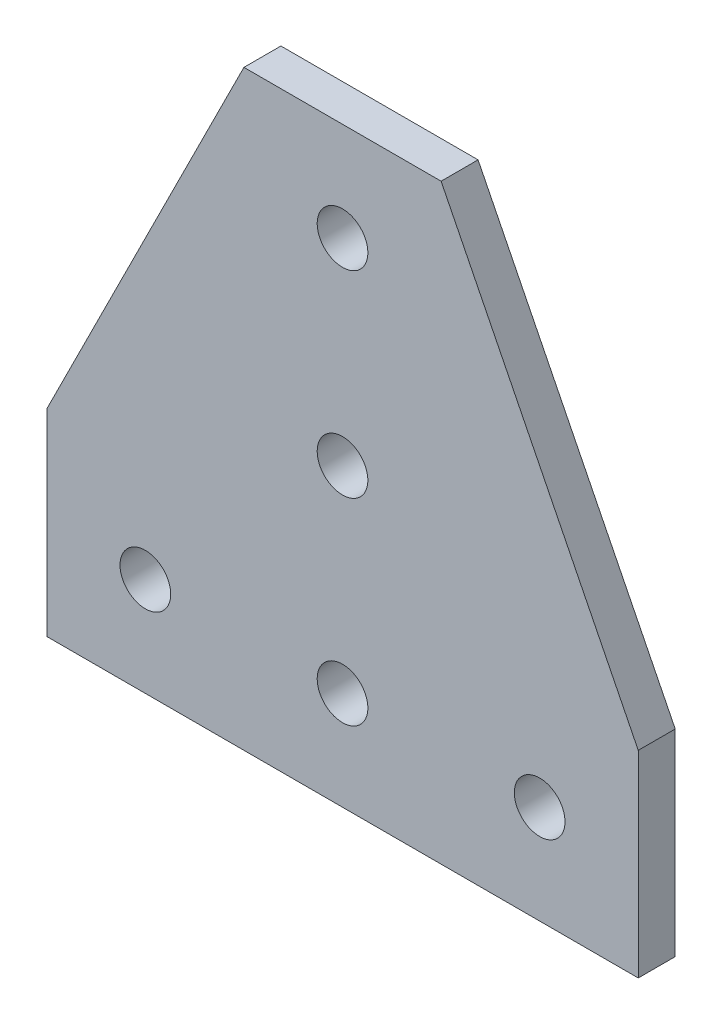
SolidWorks part; units mm, degrees
ref_plane "Front Plane" through (0, 0, 0) normal (0, 0, 1) x (1, 0, 0)
ref_plane "Top Plane" through (0, 0, 0) normal (0, 1, 0) x (1, 0, 0)
ref_plane "Right Plane" through (0, 0, 0) normal (1, 0, 0) x (0, 0, -1)
sketch "Sketch1" plane through (0, 0, 0) normal (0, 0, 1) x (1, 0, 0)
  line L0 (12.7, 25.4) -> (25.4, 25.4)
  line L1 (25.4, 25.4) -> (25.4, -50.8)
  line L2 (25.4, -50.8) -> (-12.7, -50.8)
  line L3 (-12.7, -50.8) -> (-12.7, -25.4)
  line L4 (-12.7, -25.4) -> (12.7, 25.4)
  dimension "D1" = 12.7
  dimension "height" = 76.2
  dimension "width" = 38.1
  dimension "flat" = 25.4
extrude "Extrude1" add sketch "Sketch1" against normal blind 4.7625
mirror "Mirror1" about plane through (25.4, 25.4, -4.7625) normal (1, 0, 0) of bodies 101
sketch "Sketch2" plane through (0, 0, -4.7625) normal (0, 0, -1) x (-1, 0, 0)
  line L0 (-25.4, 25.4) -> (-25.4, -38.1) construction
  line L1 (-38.1, 25.4) -> (-12.7, 25.4) construction
  line L2 (12.7, -38.1) -> (-25.4, -38.1) construction
  line L3 (12.7, -25.4) -> (12.7, -50.8) construction
  circle A0 centre (-25.4, -38.1) radius 3.2639
  circle A1 centre (0, -38.1) radius 3.2639
  circle A2 centre (25.4, -38.1) radius 3.2639
  circle A3 centre (-25.4, -12.7) radius 3.2639
  circle A4 centre (-25.4, 12.7) radius 3.2639
  dimension "hole" = 6.5278
  dimension "D2" = 25.4
  dimension "D3" = 25.4
  dimension "D4" = 25.4
  dimension "center to center" = 25.4
extrude "single 90" [suppressed] cut sketch "Sketch2" against normal through all
sketch "Sketch3" plane through (0, 0, -4.7625) normal (0, 0, -1) x (-1, 0, 0)
  line L0 (-63.5, -38.1) -> (12.7, -38.1) construction
  line L1 (-63.5, -25.4) -> (-63.5, -50.8) construction
  line L2 (12.7, -25.4) -> (12.7, -50.8) construction
  line L3 (-25.4, 25.4) -> (-25.4, -38.1) construction
  line L4 (-38.1, 25.4) -> (-12.7, 25.4) construction
  circle A0 centre (-25.4, -38.1) radius 3.2639
  circle A1 centre (-25.4, -12.7) radius 3.2639
  circle A2 centre (-25.4, 12.7) radius 3.2639
  circle A3 centre (-50.8, -38.1) radius 3.2639
  circle A4 centre (0, -38.1) radius 3.2639
  dimension "D1" = 6.5278
  dimension "D3" = 25.4
  dimension "D4" = 25.4
  dimension "D5" = 25.4
  dimension "center to center" = 25.4
extrude "single tee" cut sketch "Sketch3" against normal through all
sketch "Sketch4" [suppressed] plane through (0, 0, -6.35) normal (0, 0, -1) x (-1, 0, 0)
  line L0 (19.05, -76.2) -> (19.05, -57.15) construction
  line L1 (12.7, -25.4) -> (12.7, -50.8) construction
  line L2 (19.05, -57.15) -> (19.05, -38.1) construction
  line L3 (-114.3, 38.1) -> (-38.1, 38.1) construction
  line L4 (-38.1, 25.4) -> (-12.7, 25.4) construction
  line L5 (-38.1, 38.1) -> (-19.05, 38.1) construction
  line L6 (-76.2, 38.1) -> (-76.2, -66.675) construction
  line L7 (19.05, -66.675) -> (-76.2, -66.675) construction
  line L8 (19.05, -47.625) -> (-28.575, -47.625) construction
  line L9 (-28.575, 38.1) -> (-28.575, -47.625) construction
  circle A0 centre (-76.2, -66.675) radius 4.1656
  circle A1 centre (-28.575, -47.625) radius 4.1656
  circle A2 centre (-28.575, -66.675) radius 4.1656
  circle A3 centre (-76.2, -47.625) radius 4.1656
  circle A4 centre (-3.175, -47.625) radius 4.1656
  circle A5 centre (22.225, -47.625) radius 4.1656
  circle A6 centre (-3.175, -66.675) radius 4.1656
  circle A7 centre (22.225, -66.675) radius 4.1656
  circle A8 centre (-76.2, -22.225) radius 4.1656
  circle A9 centre (-76.2, 3.175) radius 4.1656
  circle A10 centre (-28.575, 3.175) radius 4.1656
  circle A11 centre (-28.575, -22.225) radius 4.1656
  dimension "D3" = 25.4
  dimension "D4" = 25.4
  dimension "D5" = 6.5278
  dimension "center to center" = 25.4
  dimension "D2" = 25.4
extrude "double 90" [suppressed] cut sketch "Sketch4" against normal through all
sketch "Sketch5" plane through (0, 0, -4.7625) normal (0, 0, -1) x (-1, 0, 0)
  line L0 (-25.4, 25.4) -> (-25.4, -50.8) construction
  line L1 (-38.1, 25.4) -> (-12.7, 25.4) construction
  line L2 (-25.4, 25.4) -> (-12.7, 25.4) construction
  line L3 (-19.05, 25.4) -> (-19.05, -44.45) construction
  line L4 (12.7, -50.8) -> (12.7, -38.1) construction
  line L5 (12.7, -25.4) -> (12.7, -50.8) construction
  line L6 (12.7, -38.1) -> (12.7, -25.4) construction
  line L7 (12.7, -31.75) -> (-19.05, -31.75) construction
  line L8 (12.7, -44.45) -> (-19.05, -44.45) construction
  line L9 (12.7, -50.8) -> (-63.5, -50.8) construction
  circle A0 centre (-19.05, -31.75) radius 3.2639
  circle A1 centre (-19.05, -44.45) radius 3.2639
  circle A2 centre (6.35, -44.45) radius 3.2639
  circle A3 centre (6.35, -31.75) radius 3.2639
  circle A4 centre (-19.05, -6.35) radius 3.2639
  circle A5 centre (-19.05, 19.05) radius 3.2639
  circle A6 centre (-31.75, -44.45) radius 3.2639
  circle A7 centre (-57.15, -44.45) radius 3.2639
  circle A8 centre (-57.15, -31.75) radius 3.2639
  circle A9 centre (-31.75, -31.75) radius 3.2639
  circle A10 centre (-31.75, -6.35) radius 3.2639
  circle A11 centre (-31.75, 19.05) radius 3.2639
  dimension "D2" = 25.4
  dimension "D3" = 25.4
  dimension "D1" = 6.5278
  dimension "center to center" = 25.4
extrude "double tee" [suppressed] cut sketch "Sketch5" against normal through all
equation "\"D2@Sketch2\" = \"center to center@Sketch2\""
equation "\"D3@Sketch2\" = \"center to center@Sketch2\""
equation "\"D4@Sketch2\" = \"center to center@Sketch2\""
equation "\"D1@Sketch3\" = \"hole@Sketch2\""
equation "\"D5@Sketch3\" = \"center to center@Sketch3\""
equation "\"D3@Sketch3\" = \"center to center@Sketch3\""
equation "\"D4@Sketch3\" = \"center to center@Sketch3\""
equation "\"D2@Sketch4\" = \"center to center@Sketch4\""
equation "\"D3@Sketch4\" = \"center to center@Sketch4\""
equation "\"D4@Sketch4\" = \"center to center@Sketch4\""
equation "\"D5@Sketch4\" = \"hole@Sketch2\""
equation "\"D1@Sketch5\" = \"hole@Sketch2\""
equation "\"D2@Sketch5\" = \"center to center@Sketch5\""
equation "\"D3@Sketch5\" = \"center to center@Sketch5\""
